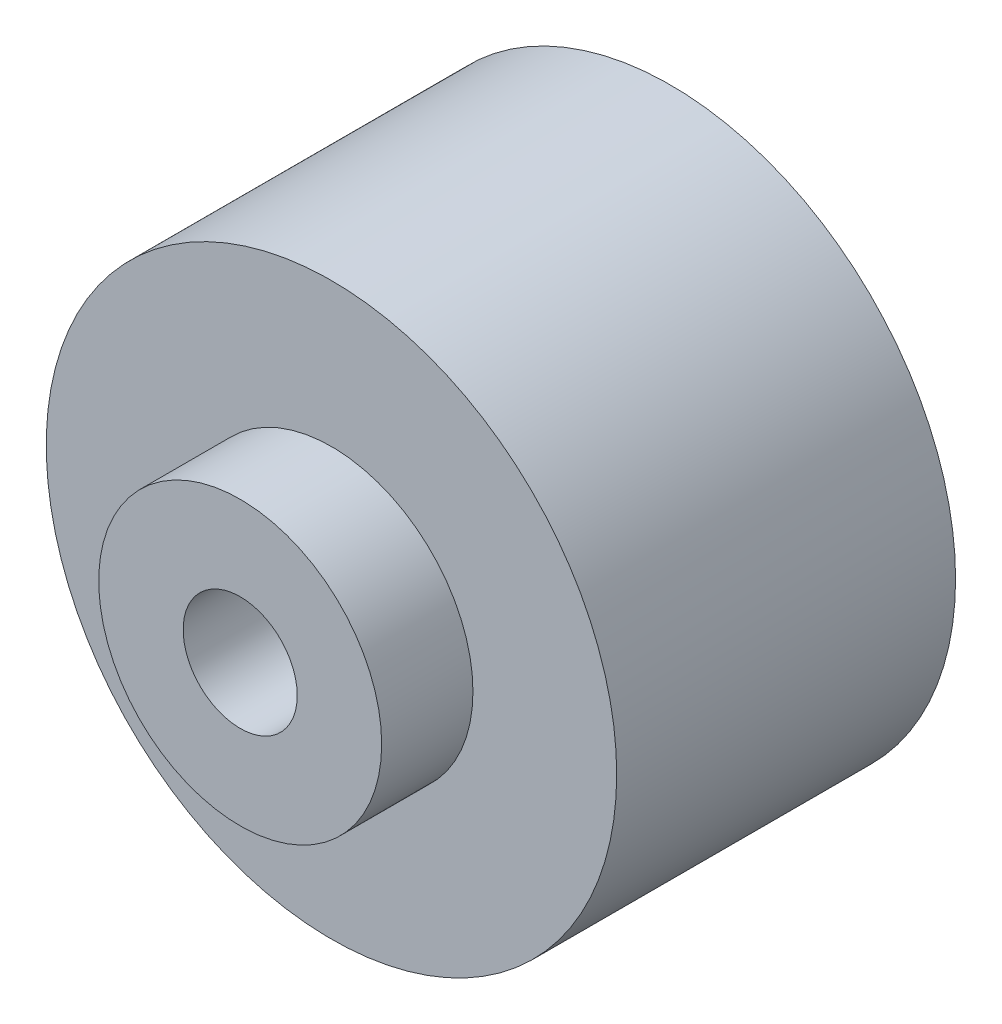
SolidWorks part; units mm, degrees
ref_plane "Ön Düzlem" through (0, 0, 0) normal (0, 0, 1) x (1, 0, 0)
ref_plane "Üst Düzlem" through (0, 0, 0) normal (0, 1, 0) x (1, 0, 0)
ref_plane "Sağ Düzlem" through (0, 0, 0) normal (1, 0, 0) x (0, 0, -1)
sketch "Çizim1" plane through (0, 0, 0) normal (0, 0, 1) x (1, 0, 0)
  circle A0 centre (0, 0) radius 25
  dimension "D1" = 50
extrude "Yükseklik-Ekstrüzyon1" add sketch "Çizim1" along normal blind 29.7
sketch "Çizim2" plane through (0, 0, 0) normal (0, 0, -1) x (-1, 0, 0)
  circle A0 centre (0, 0) radius 11
  dimension "D1" = 22
extrude "Yükseklik-Ekstrüzyon2" add sketch "Çizim2" along normal blind 6 contours A0
sketch "Çizim3" plane through (0, 0, 29.7) normal (0, 0, 1) x (1, 0, 0)
  circle A0 centre (0, 0) radius 12.4
  dimension "D1" = 24.8
extrude "Yükseklik-Ekstrüzyon3" add sketch "Çizim3" along normal blind 8
sketch "Çizim4" plane through (0, 0, 37.7) normal (0, 0, 1) x (1, 0, 0)
  circle A0 centre (0, 0) radius 5
  dimension "D1" = 10
extrude "Kes-Ekstrüzyon1" cut sketch "Çizim4" against normal through all contours A0
